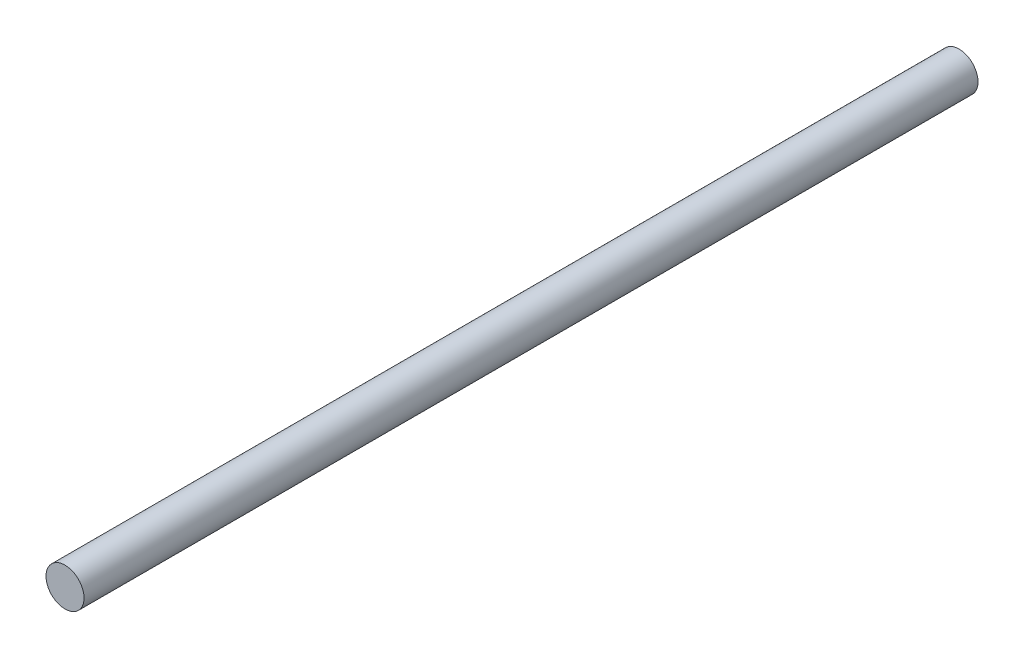
SolidWorks part; units mm, degrees
ref_plane "Front Plane" through (0, 0, 0) normal (0, 0, 1) x (1, 0, 0)
ref_plane "Top Plane" through (0, 0, 0) normal (0, 1, 0) x (1, 0, 0)
ref_plane "Right Plane" through (0, 0, 0) normal (1, 0, 0) x (0, 0, -1)
sketch "Sketch1" plane through (0, 0, 0) normal (0, 0, 1) x (1, 0, 0)
  circle A0 centre (0, 0) radius 2.5
extrude "Boss-Extrude1" add sketch "Sketch1" along normal blind 117.5
